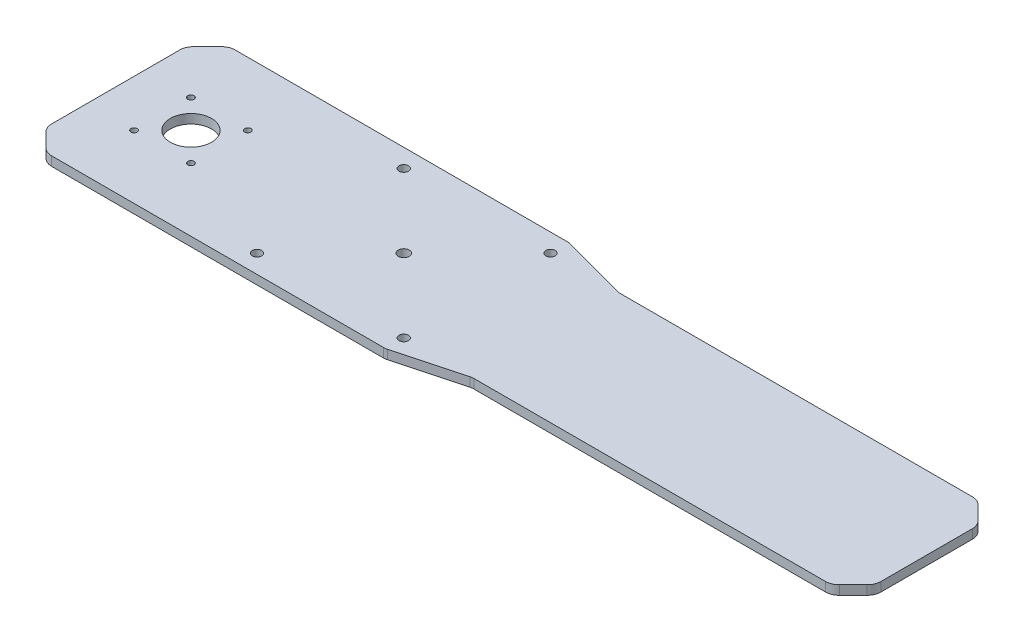
SolidWorks part; units mm, degrees
material "Alumina"
ref_plane "Front Plane" through (0, 0, 0) normal (0, 0, 1) x (1, 0, 0)
ref_plane "Top Plane" through (0, 0, 0) normal (0, 1, 0) x (1, 0, 0)
ref_plane "Right Plane" through (0, 0, 0) normal (1, 0, 0) x (0, 0, -1)
sketch "Sketch1" plane through (0, 0, 0) normal (0, 1, 0) x (1, 0, 0)
  line L0 (40, -50) -> (77.3205, -40)
  line L1 (-40, 50) -> (40, 50)
  line L2 (-40, 50) -> (-40, -50) construction
  line L3 (-40, -50) -> (40, -50)
  line L4 (40, 50) -> (40, -50) construction
  line L5 (-40, 50) -> (40, -50) construction
  line L6 (-40, -50) -> (40, 50) construction
  line L7 (-40, 50) -> (-157, 50)
  line L8 (-40, 50) -> (-40, -50) construction
  line L9 (-40, -50) -> (-157, -50)
  line L10 (-157, 50) -> (-157, -50)
  line L12 (40, 50) -> (40, -50) construction
  line L14 (40, 50) -> (77.3205, 40)
  line L16 (77.3205, 40) -> (285, 40)
  line L17 (77.3205, 40) -> (77.3205, -40) construction
  line L18 (77.3205, -40) -> (285, -40)
  line L19 (285, 40) -> (285, -40)
  point P0 (0, 0)
  point P6 (0, 0)
  point P11 (250, 0)
  dimension "D1" = 80
  dimension "D2" = 100
  dimension "D5" = 250
  dimension "D4" = 75
  dimension "D6" = 75
  dimension "D7" = 80
  dimension "D8" = 35
  dimension "D3" = 117
extrude "Boss-Extrude2" add sketch "Sketch1" along normal blind 5
chamfer "Chamfer2" distance 12 angle 45 4 edges at (-157, 2.5, 50) (-157, 2.5, -50) (285, 2.5, -40) (285, 2.5, 40)
fillet "Fillet1" radius 7.5 12 edges at (-145, 2.5, -50) (-157, 2.5, -38) (-157, 2.5, 38) (-145, 2.5, 50) (273, 2.5, 40) (285, 2.5, 28) (285, 2.5, -28) (273, 2.5, -40) (40, 2.5, 50) (77.3205, 2.5, 40) (77.3205, 2.5, -40) (40, 2.5, -50)
sketch "Sketch2" plane through (0, 5, 0) normal (0, 1, 0) x (1, 0, 0)
  line L0 (0, 50) -> (0, -50) construction
  line L1 (39.0126, 50) -> (-141.8934, 50) construction
  line L2 (-141.8934, -50) -> (39.0126, -50) construction
  line L3 (-157, 0) -> (285, 0) construction
  line L4 (-157, 34.8934) -> (-157, -34.8934) construction
  line L5 (285, -24.8934) -> (285, 24.8934) construction
  circle A0 centre (-40, 40) radius 2.575
  circle A1 centre (40, 40) radius 2.575
  circle A2 centre (40, -40) radius 2.575
  circle A3 centre (-40, -40) radius 2.575
  circle A4 centre (-116, 0) radius 11.25
  circle A5 centre (0, 0) radius 3
  dimension "D3" = 5.15
  dimension "D4" = 22.5
  dimension "D6" = 6
  dimension "D1" = 40
  dimension "D2" = 40
  dimension "D5" = 41
extrude "Cut-Extrude1" cut sketch "Sketch2" against normal through all
hole_wizard "CSK for M3 Countersunk Flat Head Screw2" positions "Sketch5" profile "Sketch4" countersink size "M3" standard "DIN" end condition through all
sketch "Sketch5" plane through (0, 0, 0) normal (0, -1, 0) x (-1, 0, 0)
  line L0 (157, 0) -> (0, 0) construction
  line L1 (157, 34.8934) -> (157, -34.8934) construction
  line L3 (116, -50) -> (116, 50) construction
  line L4 (141.8934, -50) -> (-39.0126, -50) construction
  line L5 (-39.0126, 50) -> (141.8934, 50) construction
  point P16 (131.5, -15.5)
  point P22 (100.5, -15.5)
  point P23 (100.5, 15.5)
  point P24 (131.5, 15.5)
  point P25 (0, 0)
  dimension "D5" = 41
  dimension "D3" = 15.5
  dimension "D7" = 31
  dimension "D6" = 31
  dimension "D4" = 15.5
  dimension "D1" = 2
  dimension "D2" = 2
sketch "Sketch4" plane through (-131.5, 0, -15.5) normal (1, 0, 0) x (0, 0, -1)
  line L0 (0, 0) -> (0, 5)
  line L1 (0, 5) -> (1.7, 5)
  line L2 (1.7, 5) -> (1.7, 1.45)
  line L3 (1.7, 1.45) -> (3.15, 0)
  line L5 (3.15, 0) -> (0, 0)
  line L6 (-1.7, 1.45) -> (-3.15, 0) construction
  line L11 (0, -6.35) -> (0, 107.95) construction
  dimension "Thru Hole Dia." = 3.4
  dimension "Thru Hole Depth" = 5
  dimension "Near C'Sink Dia." = 6.3
  dimension "Near C'Sink Angle" = 90
equation "\"Elevator Guide Rod Distance\"= 80mm"
equation "\"Extra Spacing\"= 20mm"
equation "\"Plate Thickness\"= 5mm"
equation "\"D1@Sketch1\"=\"Elevator Guide Rod Distance\""
equation "\"D2@Sketch1\"=\"Elevator Guide Rod Distance\"+\"Extra Spacing\""
equation "\"Elevator Servo Offset\"= 75mm"
equation "\"Servo Width\"= 42mm"
equation "\"Pivot Point End Offset\"= 35mm"
equation "\"Origin Pivot Distance\"= 250mm"
equation "\"D5@Sketch1\"=\"Origin Pivot Distance\""
equation "\"Narrow Section Width\"= 80mm"
equation "\"D7@Sketch1\"=\"Narrow Section Width\""
equation "\"D8@Sketch1\"=\"Pivot Point End Offset\""
equation "\"D1@Sketch2\"=\"Elevator Guide Rod Distance\"/2"
equation "\"D2@Sketch2\"=\"Elevator Guide Rod Distance\"/2"
equation "\"Guide Rod Diameter\"= 5mm"
equation "\"D3@Sketch2\"=\"Guide Rod Diameter\"+.15"
equation "\"Servo Hole X-Offset\"= 15.5mm"
equation "\"Servo Hole Y-Offset\" = 15.5mm"
equation "\"D1@3DSketch2\"=\"Servo Width\"/2+\"Extra Spacing\""
equation "\"D3@Sketch5\"=\"Servo Hole Y-Offset\""
equation "\"D5@Sketch5\"=\"Servo Width\"/2 + \"Extra Spacing\""
equation "\"D7@Sketch5\"=\"Servo Hole Y-Offset\"*2"
equation "\"D6@Sketch5\"=\"Servo Hole X-Offset\"*2 "
equation "\"D4@Sketch5\"=\"Servo Hole X-Offset\""
equation "\"Servo Shaft Diameter\"= 22.5mm"
equation "\"D5@Sketch2\"=\"Servo Width\" / 2 + \"Extra Spacing\""
equation "\"D4@Sketch2\"=\"Servo Shaft Diameter\""
equation "\"Elevator Screw Lift Diameter\"= 6mm"
equation "\"D6@Sketch2\"=\"Elevator Screw Lift Diameter\""
equation "\"D3@Sketch1\"=\"Servo Width\" + \"Extra Spacing\" * 2 + 35"
